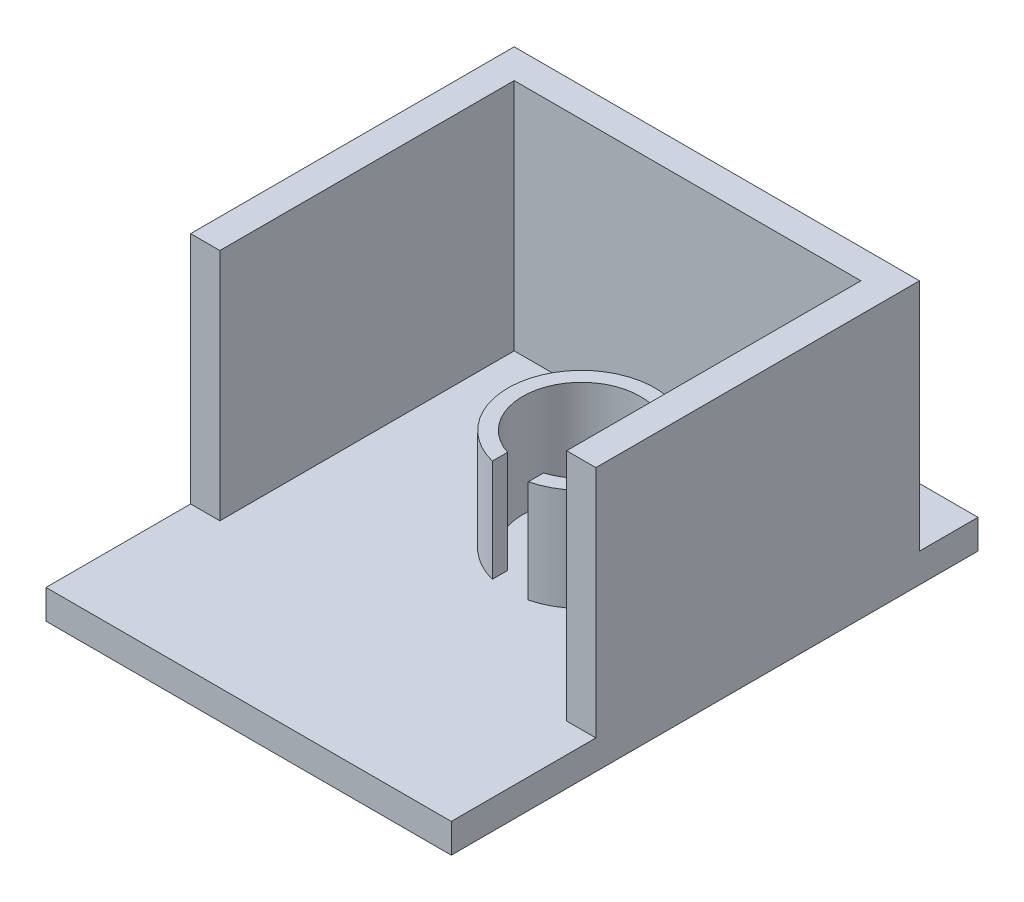
SolidWorks part; units mm, degrees
ref_plane "Front Plane" through (0, 0, 0) normal (0, 0, 1) x (1, 0, 0)
ref_plane "Top Plane" through (0, 0, 0) normal (0, 1, 0) x (1, 0, 0)
ref_plane "Right Plane" through (0, 0, 0) normal (1, 0, 0) x (0, 0, -1)
sketch "Sketch1" plane through (0, 0, 0) normal (0, 1, 0) x (1, 0, 0)
  line L1 (-80, -80) -> (80, -80)
  line L2 (-80, -80) -> (-80, 80)
  line L3 (-80, 80) -> (80, 80)
  line L4 (80, -80) -> (80, 80)
  line L5 (-80, -80) -> (80, 80) construction
  line L6 (-80, 80) -> (80, -80) construction
  point P0 (0, 0)
  dimension "D1" = 160
  dimension "D2" = 160
extrude "Boss-Extrude1" add sketch "Sketch1" along normal mid plane 10
sketch "Sketch3" plane through (0, 5, 0) normal (0, 1, 0) x (1, 0, 0)
  line L0 (-80, 80) -> (48.5, 80) construction
  line L1 (80, 80) -> (-80, 80) construction
  line L2 (48.5, 80) -> (48.5, 74) construction
  line L3 (48.5, 74) -> (-48.5, 74) construction
  line L4 (0, 74) -> (0, 23) construction
  line L6 (-52, 23) -> (-72, 23) construction
  line L7 (0, 80) -> (0, -55)
  line L8 (0, 23) -> (-52, 23) construction
  line L9 (-52, 23) -> (-52, 63.419)
  line L10 (-52, 63.419) -> (-52, -30.581)
  circle A0 centre (0, 23) radius 43.5
  dimension "D5" = 87
  dimension "D1" = 128.5
  dimension "D2" = 6
  dimension "D3" = 97
  dimension "D4" = 51
  dimension "D7" = 135
  dimension "D8" = 52
  dimension "D9" = 94
  dimension "D10" = 20
sketch "Sketch17" plane through (0, 5, 0) normal (0, 1, 0) x (1, 0, 0)
  line L0 (0, 80) -> (0, -55) construction
  line L1 (0, 23) -> (-52, 23) construction
  line L4 (-6.1352, 3.8592) -> (-6.1352, -1.3386)
  line L5 (6.1352, 3.8592) -> (6.1352, -1.3386)
  arc A0 (6.1352, 3.8592) -> (-6.1352, 3.8592) centre (0, 23) ccw
  arc A1 (6.1352, -1.3386) -> (-6.1352, -1.3386) centre (0, 23) ccw
  dimension "D1" = 40.2
  dimension "D2" = 50.2
  dimension "D4" = 12.2703
extrude "Boss-Extrude8" add sketch "Sketch17" along normal blind 35
sketch "Sketch19" plane through (0, 5, 0) normal (0, 1, 0) x (1, 0, 0)
  line L0 (-80, 70) -> (-70, 70) construction
  line L1 (-80, 80) -> (-80, -80) construction
  line L2 (48.5, 74) -> (48.5, 25.827) construction
  line L3 (-80, 80) -> (48.5, 80) construction
  line L4 (-80, 80) -> (-80, -30.581)
  line L6 (-70, 70) -> (-70, -30.581)
  line L11 (-80, 80) -> (-70, 80)
  line L14 (-80, -80) -> (80, -80) construction
  line L15 (-70, -70) -> (70, -70) construction
  line L16 (70, 70) -> (70, -70) construction
  line L17 (80, 80) -> (80, -80) construction
  line L18 (-70, 70) -> (70, 70) construction
  line L19 (-80, 80) -> (80, 80) construction
  line L20 (-70, -30.581) -> (-80, -30.581)
  line L21 (48.5, -30.581) -> (58.5, -30.581)
  line L22 (48.5, 70) -> (48.5, 25.827)
  line L23 (-70, 70) -> (48.5, 70)
  line L24 (48.5, 25.827) -> (48.5, -30.581)
  line L25 (58.5, 74) -> (58.5, 25.827)
  line L26 (58.5, 25.827) -> (58.5, -30.581)
  line L27 (58.5, 74) -> (58.5, 80)
  line L28 (80, 80) -> (-80, 80) construction
  line L29 (58.5, 80) -> (-70, 80)
  line L30 (-70, 70) -> (-70, -70) construction
  line L31 (-80, 80) -> (-80, -80) construction
  dimension "D1" = 10
  dimension "D2" = 10
  dimension "D4" = 10
  dimension "D5" = 10
extrude "Boss-Extrude11" add sketch "Sketch19" along normal blind 80
sketch "Sketch23" plane through (0, 0, -80) normal (0, 0, -1) x (-1, 0, 0)
  line L1 (-80, 5) -> (80, 5)
  line L2 (-80, 5) -> (-80, -5)
  line L3 (-80, -5) -> (80, -5)
  line L4 (80, 5) -> (80, -5)
extrude "Boss-Extrude12" add sketch "Sketch23" along normal blind 20
sketch "Sketch25" plane through (0, 5, 0) normal (0, 1, 0) x (1, 0, 0)
  line L0 (-80, 100) -> (80, 100) construction
  line L1 (80, -80) -> (58.5, -80)
  line L2 (80, -80) -> (80, 100)
  line L3 (80, 100) -> (58.5, 100)
  line L4 (58.5, -80) -> (58.5, 100)
extrude "Cut-Extrude4" cut sketch "Sketch25" against normal blind 10
